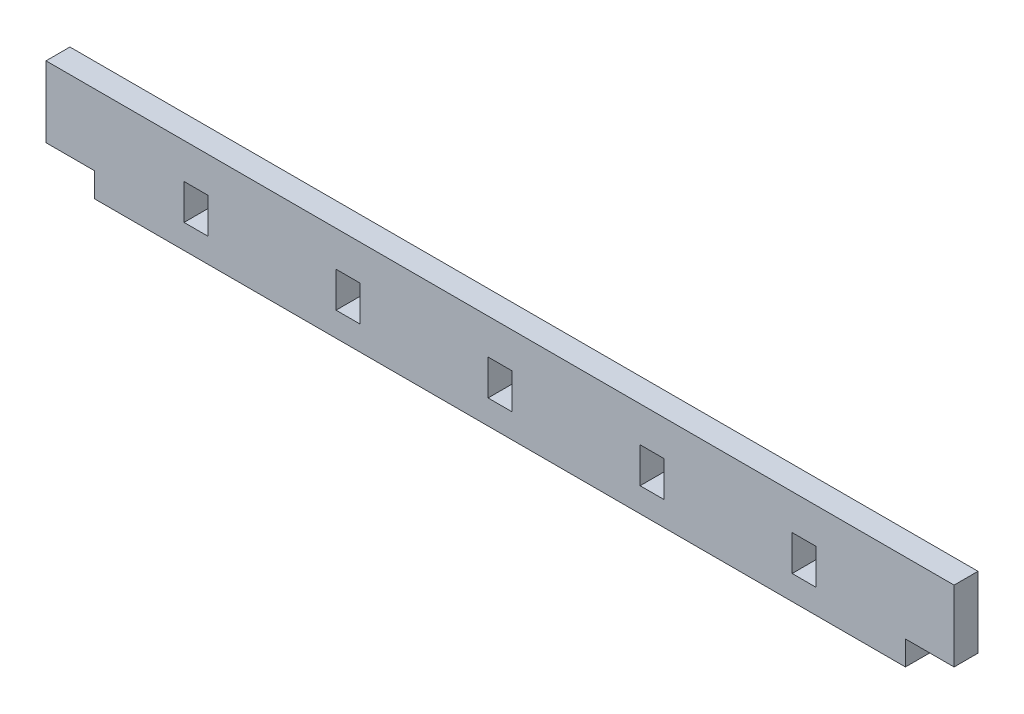
SolidWorks part; units mm, degrees
ref_plane "Front Plane" through (0, 0, 0) normal (0, 0, 1) x (1, 0, 0)
ref_plane "Top Plane" through (0, 0, 0) normal (0, 1, 0) x (1, 0, 0)
ref_plane "Right Plane" through (0, 0, 0) normal (1, 0, 0) x (0, 0, -1)
sketch "Sketch1" plane through (0, 0, 0) normal (0, 0, 1) x (1, 0, 0)
  line L0 (0, 19.2778) -> (0, 10.3878) construction
  line L1 (6.096, 19.2778) -> (0, 19.2778) construction
  line L2 (6.096, 10.3878) -> (0, 10.3878) construction
  line L3 (20.2946, 14.8328) -> (17.2974, 14.8328) construction
  line L4 (20.2946, 10.3878) -> (20.2946, 14.8328) construction
  line L5 (17.2974, 10.3878) -> (17.2974, 14.8328) construction
  line L6 (20.2946, 10.3878) -> (17.2974, 10.3878) construction
  line L7 (39.3446, 10.3878) -> (36.3474, 10.3878) construction
  line L8 (36.3474, 10.3878) -> (36.3474, 14.8328) construction
  line L9 (39.3446, 14.8328) -> (36.3474, 14.8328) construction
  line L10 (39.3446, 10.3878) -> (39.3446, 14.8328) construction
  line L11 (55.3974, 10.3878) -> (55.3974, 14.8328) construction
  line L12 (58.3946, 14.8328) -> (55.3974, 14.8328) construction
  line L13 (58.3946, 10.3878) -> (58.3946, 14.8328) construction
  line L14 (58.3946, 10.3878) -> (55.3974, 10.3878) construction
  line L15 (77.4446, 10.3878) -> (74.4474, 10.3878) construction
  line L16 (77.4446, 10.3878) -> (77.4446, 14.8328) construction
  line L17 (77.4446, 14.8328) -> (74.4474, 14.8328) construction
  line L18 (74.4474, 10.3878) -> (74.4474, 14.8328) construction
  line L19 (96.4946, 10.3878) -> (93.4974, 10.3878) construction
  line L20 (93.4974, 10.3878) -> (93.4974, 14.8328) construction
  line L21 (96.4946, 14.8328) -> (93.4974, 14.8328) construction
  line L22 (96.4946, 10.3878) -> (96.4946, 14.8328) construction
  line L23 (113.792, 19.2778) -> (107.696, 19.2778) construction
  line L24 (113.792, 19.2778) -> (113.792, 10.3878) construction
  line L25 (113.792, 10.3878) -> (107.696, 10.3878) construction
  line L26 (0, 19.2778) -> (0, 10.3878)
  line L27 (6.096, 19.2778) -> (0, 19.2778)
  line L28 (6.096, 10.3878) -> (0, 10.3878)
  line L29 (20.2946, 14.8328) -> (17.2974, 14.8328)
  line L30 (20.2946, 10.3878) -> (20.2946, 14.8328)
  line L31 (17.2974, 10.3878) -> (17.2974, 14.8328)
  line L32 (20.2946, 10.3878) -> (17.2974, 10.3878)
  line L33 (39.3446, 10.3878) -> (36.3474, 10.3878)
  line L34 (36.3474, 10.3878) -> (36.3474, 14.8328)
  line L35 (39.3446, 14.8328) -> (36.3474, 14.8328)
  line L36 (39.3446, 10.3878) -> (39.3446, 14.8328)
  line L37 (55.3974, 10.3878) -> (55.3974, 14.8328)
  line L38 (58.3946, 14.8328) -> (55.3974, 14.8328)
  line L39 (58.3946, 10.3878) -> (58.3946, 14.8328)
  line L40 (58.3946, 10.3878) -> (55.3974, 10.3878)
  line L41 (77.4446, 10.3878) -> (74.4474, 10.3878)
  line L42 (77.4446, 10.3878) -> (77.4446, 14.8328)
  line L43 (77.4446, 14.8328) -> (74.4474, 14.8328)
  line L44 (74.4474, 10.3878) -> (74.4474, 14.8328)
  line L45 (96.4946, 10.3878) -> (93.4974, 10.3878)
  line L46 (93.4974, 10.3878) -> (93.4974, 14.8328)
  line L47 (96.4946, 14.8328) -> (93.4974, 14.8328)
  line L48 (96.4946, 10.3878) -> (96.4946, 14.8328)
  line L49 (113.792, 19.2778) -> (107.696, 19.2778)
  line L50 (113.792, 19.2778) -> (113.792, 10.3878)
  line L51 (113.792, 10.3878) -> (107.696, 10.3878)
  line L52 (6.096, 19.2778) -> (107.696, 19.2778)
  line L53 (107.696, 10.3878) -> (107.696, 7.3398)
  line L55 (107.696, 7.3398) -> (6.096, 7.3398)
  line L56 (6.096, 7.3398) -> (6.096, 10.3878)
  dimension "D1" = 3.048
extrude "Boss-Extrude1" add sketch "Sketch1" along normal blind 2.9972
